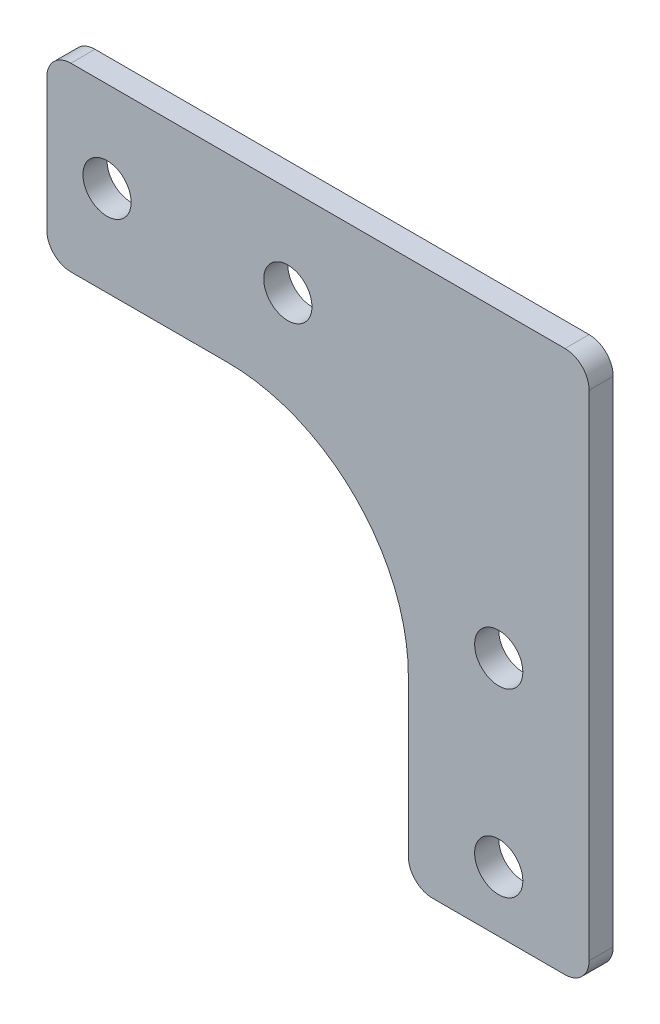
SolidWorks part; units mm, degrees
ref_plane "前视基准面" through (0, 0, 0) normal (0, 0, 1) x (1, 0, 0)
ref_plane "上视基准面" through (0, 0, 0) normal (0, 1, 0) x (1, 0, 0)
ref_plane "右视基准面" through (0, 0, 0) normal (1, 0, 0) x (0, 0, -1)
sketch "草图1" plane through (0, 0, 0) normal (0, 0, 1) x (1, 0, 0)
  line L0 (0, 0) -> (0, -45)
  line L1 (0, -45) -> (-15, -45)
  line L2 (-15, -45) -> (-15, -30)
  line L3 (-30, -15) -> (-45, -15)
  line L4 (-45, -15) -> (-45, 0)
  line L5 (-45, 0) -> (0, 0)
  arc A0 (-15, -30) -> (-30, -15) centre (-30, -30) ccw
  dimension "D5" = 15
  dimension "D1" = 15
  dimension "D2" = 15
  dimension "D3" = 45
  dimension "D4" = 45
extrude "凸台-拉伸1" add sketch "草图1" along normal blind 2
sketch "草图2" plane through (0, 0, 2) normal (0, 0, 1) x (1, 0, 0)
  line L0 (0, 0) -> (-45, 0) construction
  line L2 (0, -45) -> (0, 0) construction
  line L4 (0, 0) -> (-45, 0) construction
  circle A0 centre (-7.5, -40) radius 2
  circle A1 centre (-7.5, -25) radius 2
  circle A2 centre (-25, -7.5) radius 2
  circle A3 centre (-40, -7.5) radius 2
  dimension "D1" = 4
  dimension "D2" = 25
  dimension "D5" = 15
  dimension "D6" = 25
  dimension "D3" = 15
  dimension "D4" = 7.5
  dimension "D7" = 7.5
extrude "切除-拉伸1" cut sketch "草图2" against normal blind 2
fillet "圆角1" radius 2 5 edges at (0, -45, 1) (0, 0, 1) (-15, -45, 1) (-45, -15, 1) (-45, 0, 1)
